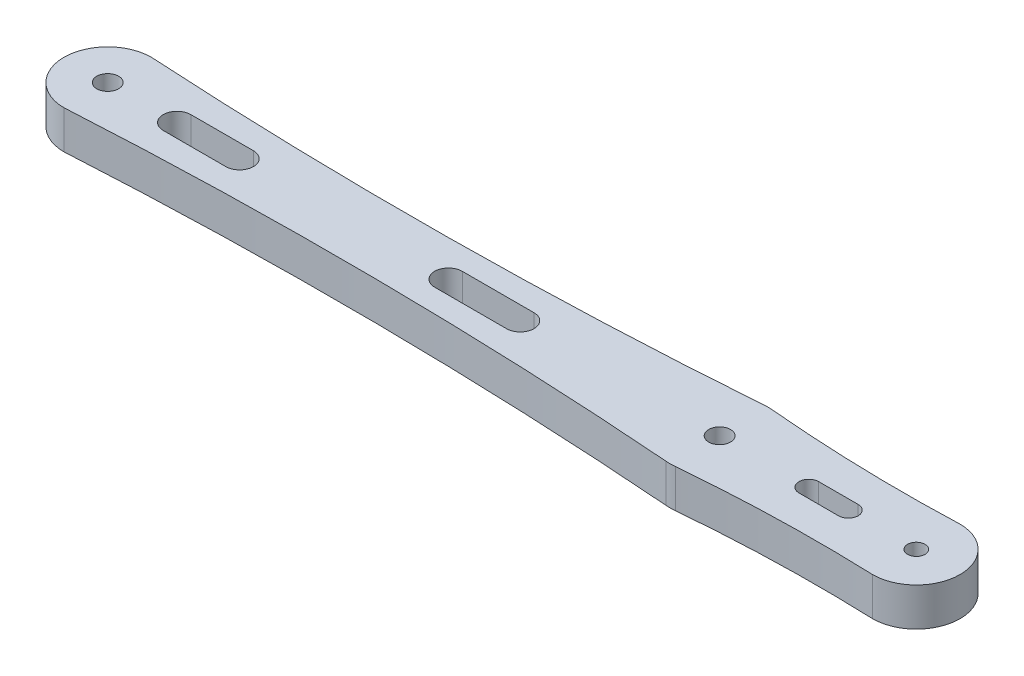
SolidWorks part; units mm, degrees
ref_plane "Ön Düzlem" through (0, 0, 0) normal (0, 0, 1) x (1, 0, 0)
ref_plane "Üst Düzlem" through (0, 0, 0) normal (0, 1, 0) x (1, 0, 0)
ref_plane "Sağ Düzlem" through (0, 0, 0) normal (1, 0, 0) x (0, 0, -1)
sketch "Sketch1" plane through (0, 0, 0) normal (0, 1, 0) x (1, 0, 0)
  line L0 (-112, 0) -> (36, 0) construction
  circle A0 centre (0, 0) radius 9
  circle A1 centre (0, 0) radius 2
  circle A2 centre (36, 0) radius 1.6
  circle A3 centre (36, 0) radius 8
  circle A4 centre (-112, 0) radius 2
  circle A5 centre (-112, 0) radius 8
  arc A6 (-112, 8) -> (0, 9) centre (-63.3603, 832.8576) ccw
  arc A7 (0, 9) -> (36, 8) centre (25.6437, 283.6726) ccw
  arc A8 (0, -9) -> (36, -8) centre (25.6437, -283.6726) cw
  arc A9 (-112, -8) -> (0, -9) centre (-63.3603, -832.8576) cw
  dimension "D1" = 16
  dimension "D2" = 4
  dimension "D3" = 18
  dimension "D4" = 4
  dimension "D5" = 3.2
  dimension "D6" = 16
  dimension "D7" = 36
  dimension "D8" = 112
extrude "Boss-Extrude1" add sketch "Sketch1" along normal blind 7
fillet "Fillet1" radius 10 2 edges at (0, 3.5, 9) (0, 3.5, -9)
sketch "Sketch2" plane through (0, 7, 0) normal (0, 1, 0) x (1, 0, 0)
  line L0 (-99.3093, 0) -> (-87.854, 0) construction
  line L1 (-99.3093, 2.5242) -> (-87.854, 2.5242)
  line L2 (-99.3093, -2.5242) -> (-87.854, -2.5242)
  line L3 (-49.6295, 0) -> (-36.486, 0) construction
  line L4 (-49.6295, 2.5242) -> (-36.486, 2.5242)
  line L5 (-49.6295, -2.5242) -> (-36.486, -2.5242)
  line L6 (16.329, 0) -> (23.5639, 0) construction
  line L7 (16.329, 1.8008) -> (23.5639, 1.8008)
  line L8 (16.329, -1.8008) -> (23.5639, -1.8008)
  arc A0 (-99.3093, 2.5242) -> (-99.3093, -2.5242) centre (-99.3093, 0) ccw
  arc A1 (-87.854, -2.5242) -> (-87.854, 2.5242) centre (-87.854, 0) ccw
  arc A2 (-49.6295, 2.5242) -> (-49.6295, -2.5242) centre (-49.6295, 0) ccw
  arc A3 (-36.486, -2.5242) -> (-36.486, 2.5242) centre (-36.486, 0) ccw
  arc A4 (16.329, 1.8008) -> (16.329, -1.8008) centre (16.329, 0) ccw
  arc A5 (23.5639, -1.8008) -> (23.5639, 1.8008) centre (23.5639, 0) ccw
  point P3 (-93.5817, 0)
  point P8 (-43.0577, 0)
  point P15 (19.9465, 0)
extrude "Cut-Extrude1" cut sketch "Sketch2" against normal blind 7
